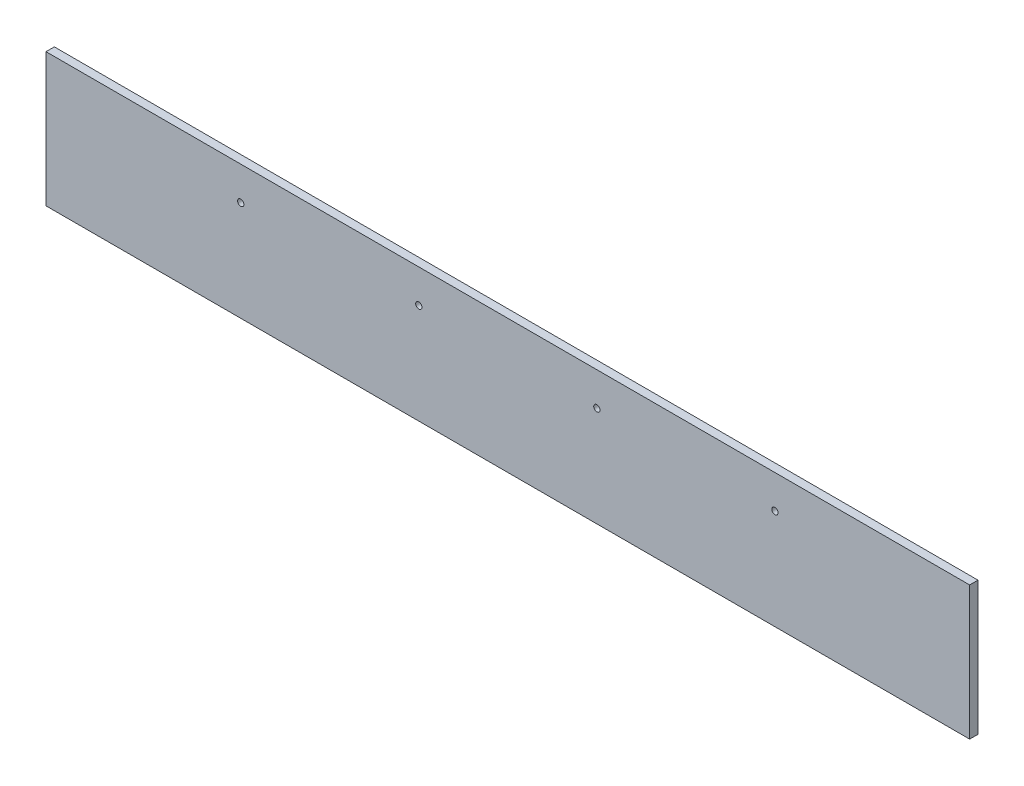
SolidWorks part; units mm, degrees
material "Custom Plastic"
ref_plane "Front Plane" through (0, 0, 0) normal (0, 0, 1) x (1, 0, 0)
ref_plane "Top Plane" through (0, 0, 0) normal (0, 1, 0) x (1, 0, 0)
ref_plane "Right Plane" through (0, 0, 0) normal (1, 0, 0) x (0, 0, -1)
sketch "Sketch2" plane through (0, 0, 0) normal (0, 1, 0) x (1, 0, 0)
  line L1 (-567.5397, 612.5757) -> (505.6103, 612.5757)
  line L2 (-567.5397, 612.5757) -> (-567.5397, -460.5743)
  line L3 (-567.5397, -460.5743) -> (505.6103, -460.5743)
  line L4 (505.6103, 612.5757) -> (505.6103, -460.5743)
  line L5 (-567.5397, 612.5757) -> (505.6103, -460.5743) construction
  line L6 (-567.5397, -460.5743) -> (505.6103, 612.5757) construction
  line L11 (-532.6147, -425.6493) -> (470.6853, 577.6507) construction
  line L12 (-532.6147, 577.6507) -> (470.6853, -425.6493) construction
  point P0 (-30.9647, 76.0007)
  point P5 (-30.9647, 76.0007)
extrude "Boss-Extrude2" add sketch "Sketch2" along normal blind 152.4 contours L1 L4 L3 L2
sketch "Sketch6" plane through (0, 152.4, 0) normal (0, 1, 0) x (1, 0, 0)
  line L17 (-567.5397, -460.5743) -> (505.6103, -460.5743) construction
  line L18 (-567.5397, -460.5743) -> (505.6103, -460.5743)
  line L19 (-567.5397, 612.5757) -> (-567.5397, -460.5743) construction
  line L20 (-567.5397, 612.5757) -> (-567.5397, -460.5743)
  line L21 (-567.5397, 612.5757) -> (505.6103, 612.5757) construction
  line L22 (-567.5397, 612.5757) -> (505.6103, 612.5757)
  line L23 (505.6103, 612.5757) -> (505.6103, -460.5743) construction
  line L24 (505.6103, 612.5757) -> (505.6103, -460.5743)
  line L25 (-558.0147, 603.0507) -> (-558.0147, -451.0493)
  line L26 (-558.0147, 603.0507) -> (496.0853, 603.0507)
  line L28 (496.0853, 603.0507) -> (496.0853, -451.0493)
  line L30 (-558.0147, -451.0493) -> (496.0853, -451.0493)
  dimension "D1" = 9.525
  dimension "D2" = 9.525
extrude "Cut-Extrude3" cut sketch "Sketch6" against normal blind 142.875 contours L28 L30 L25 L26
sketch "Sketch7" plane through (0, 9.525, 0) normal (0, 1, 0) x (1, 0, 0)
  line L10 (353.2103, 460.1757) -> (353.2103, -308.1743)
  line L11 (-415.1397, -308.1743) -> (353.2103, -308.1743)
  line L12 (-415.1397, 460.1757) -> (353.2103, 460.1757)
  line L13 (-415.1397, 460.1757) -> (-415.1397, -308.1743)
extrude "Cut-Extrude4" cut sketch "Sketch7" against normal blind 142.875 contours L12 L10 L11 L13
sketch "Sketch8" plane through (0, 0, 460.5743) normal (0, 0, 1) x (1, 0, 0)
  line L2 (-567.5397, 152.4) -> (505.6103, 152.4) construction
  line L3 (505.6103, 152.4) -> (505.6103, 0) construction
  circle A12 centre (273.8353, 114.3) radius 3.5687
  circle A13 centre (70.6353, 114.3) radius 3.5687
  circle A14 centre (-132.5647, 114.3) radius 3.5687
  circle A15 centre (-335.7647, 114.3) radius 3.5687
  dimension "D1" = 38.1
  dimension "D2" = 231.775
  dimension "D3" = 203.2
  dimension "D4" = 203.2
  dimension "D5" = 203.2
extrude "Cut-Extrude5" cut sketch "Sketch8" against normal blind 1270
sketch "Sketch9" plane through (-567.5397, 0, 0) normal (-1, 0, 0) x (0, 0, 1)
  line L0 (-612.5757, 152.4) -> (460.5743, 152.4) construction
  line L1 (460.5743, 152.4) -> (460.5743, 0) construction
  line L2 (-612.5757, 152.4) -> (-612.5757, 0) construction
  circle A0 centre (295.4743, 114.3) radius 2.5006
  circle A1 centre (146.8843, 114.3) radius 2.5006
  circle A2 centre (-1.7057, 114.3) radius 2.5006
  circle A3 centre (-150.2957, 114.3) radius 2.5006
  circle A4 centre (-298.8857, 114.3) radius 2.5006
  circle A5 centre (-447.4757, 114.3) radius 2.5006
  dimension "D1" = 38.1
  dimension "D2" = 165.1
  dimension "D3" = 165.1
extrude "Cut-Extrude6" cut sketch "Sketch9" against normal blind 1270
sketch "Sketch10" plane through (0, 0, 0) normal (0, -1, 0) x (1, 0, 0)
  line L2 (-415.1397, -460.1757) -> (-415.1397, 308.1743) construction
  line L3 (-415.1397, -460.1757) -> (-415.1397, 308.1743)
  line L4 (-415.1397, -460.1757) -> (353.2103, -460.1757) construction
  line L5 (-415.1397, -460.1757) -> (353.2103, -460.1757)
  line L6 (353.2103, -460.1757) -> (353.2103, 308.1743) construction
  line L7 (353.2103, -460.1757) -> (353.2103, 308.1743)
  line L8 (-415.1397, 308.1743) -> (-567.5397, 460.5743)
  line L9 (-567.5397, 460.5743) -> (-567.5397, -612.5757)
  line L10 (-567.5397, -612.5757) -> (505.6103, -612.5757)
  line L11 (505.6103, -612.5757) -> (505.6103, 460.5743)
  line L12 (505.6103, 460.5743) -> (353.2103, 308.1743)
extrude "Cut-Extrude7" cut sketch "Sketch10" against normal blind 1016
sketch "Sketch11" plane through (0, 9.525, 0) normal (0, 1, 0) x (1, 0, 0)
  line L0 (-567.5397, -460.5743) -> (-558.0147, -451.0493) construction
  line L1 (-567.5397, -460.5743) -> (-558.0147, -451.0493)
  line L2 (-567.5397, -460.5743) -> (505.6103, -460.5743) construction
  line L3 (-567.5397, -460.5743) -> (-558.0147, -460.5743)
  line L4 (-558.0147, -451.0493) -> (-558.0147, -460.5743)
  line L5 (496.0853, -451.0493) -> (505.6103, -460.5743) construction
  line L6 (496.0853, -451.0493) -> (505.6103, -460.5743)
  line L7 (496.0853, -451.0493) -> (496.0853, -460.5743)
  line L8 (496.0853, -460.5743) -> (505.6103, -460.5743)
extrude "Cut-Extrude8" cut sketch "Sketch11" against normal blind 10.16 and the other way blind 154.94
hole_wizard "CSK for 1/4 Flat Head Machine Screw (100)1" positions "3DSketch1" profile "Sketch12" countersink size "1/4" standard "ANSI Inch" end condition through all
sketch3d "3DSketch1"
  line L0 (273.8353, 114.3, 451.0493) -> (273.8353, 114.3, 460.5743) construction
  point P0 (273.8353, 114.3, 451.0493)
sketch "Sketch12" plane through (273.8353, 114.3, 451.0493) normal (1, 0, 0) x (0, 1, 0)
  line L0 (0, 0) -> (0, 9.525)
  line L1 (0, 9.525) -> (3.3782, 9.525)
  line L2 (3.3782, 9.525) -> (3.3782, 4.0922)
  line L3 (3.3782, 4.0922) -> (8.2551, 0)
  line L5 (8.2551, 0) -> (0, 0)
  line L6 (-3.3782, 4.0922) -> (-8.2551, 0) construction
  line L11 (0, -6.35) -> (0, 107.95) construction
  dimension "Thru Hole Dia." = 6.7564
  dimension "Thru Hole Depth" = 9.525
  dimension "Near C'Sink Dia." = 16.5103
  dimension "Near C'Sink Angle" = 100
hole_wizard "CSK for 1/4 Flat Head Machine Screw (100)2" positions "3DSketch2" profile "Sketch13" countersink size "1/4" standard "ANSI Inch" end condition through all
sketch3d "3DSketch2"
  line L0 (70.6353, 114.3, 451.0493) -> (70.6353, 114.3, 460.5743) construction
  point P0 (70.6353, 114.3, 451.0493)
sketch "Sketch13" plane through (70.6353, 114.3, 451.0493) normal (1, 0, 0) x (0, 1, 0)
  line L0 (0, 0) -> (0, 9.525)
  line L1 (0, 9.525) -> (3.3782, 9.525)
  line L2 (3.3782, 9.525) -> (3.3782, 4.0922)
  line L3 (3.3782, 4.0922) -> (8.2551, 0)
  line L5 (8.2551, 0) -> (0, 0)
  line L6 (-3.3782, 4.0922) -> (-8.2551, 0) construction
  line L11 (0, -6.35) -> (0, 107.95) construction
  dimension "Thru Hole Dia." = 6.7564
  dimension "Thru Hole Depth" = 9.525
  dimension "Near C'Sink Dia." = 16.5103
  dimension "Near C'Sink Angle" = 100
hole_wizard "CSK for 1/4 Flat Head Machine Screw (100)3" positions "3DSketch3" profile "Sketch14" countersink size "1/4" standard "ANSI Inch" end condition through all
sketch3d "3DSketch3"
  line L0 (-132.5647, 114.3, 451.0493) -> (-132.5647, 114.3, 460.5743) construction
  point P0 (-132.5647, 114.3, 451.0493)
sketch "Sketch14" plane through (-132.5647, 114.3, 451.0493) normal (1, 0, 0) x (0, 1, 0)
  line L0 (0, 0) -> (0, 9.525)
  line L1 (0, 9.525) -> (3.3782, 9.525)
  line L2 (3.3782, 9.525) -> (3.3782, 4.0922)
  line L3 (3.3782, 4.0922) -> (8.2551, 0)
  line L5 (8.2551, 0) -> (0, 0)
  line L6 (-3.3782, 4.0922) -> (-8.2551, 0) construction
  line L11 (0, -6.35) -> (0, 107.95) construction
  dimension "Thru Hole Dia." = 6.7564
  dimension "Thru Hole Depth" = 9.525
  dimension "Near C'Sink Dia." = 16.5103
  dimension "Near C'Sink Angle" = 100
hole_wizard "CSK for 1/4 Flat Head Machine Screw (100)4" positions "3DSketch4" profile "Sketch15" countersink size "1/4" standard "ANSI Inch" end condition through all
sketch3d "3DSketch4"
  line L0 (-335.7647, 114.3, 451.0493) -> (-335.7647, 114.3, 460.5743) construction
  point P0 (-335.7647, 114.3, 451.0493)
sketch "Sketch15" plane through (-335.7647, 114.3, 451.0493) normal (1, 0, 0) x (0, 1, 0)
  line L0 (0, 0) -> (0, 9.525)
  line L1 (0, 9.525) -> (3.3782, 9.525)
  line L2 (3.3782, 9.525) -> (3.3782, 4.0922)
  line L3 (3.3782, 4.0922) -> (8.2551, 0)
  line L5 (8.2551, 0) -> (0, 0)
  line L6 (-3.3782, 4.0922) -> (-8.2551, 0) construction
  line L11 (0, -6.35) -> (0, 107.95) construction
  dimension "Thru Hole Dia." = 6.7564
  dimension "Thru Hole Depth" = 9.525
  dimension "Near C'Sink Dia." = 16.5103
  dimension "Near C'Sink Angle" = 100
